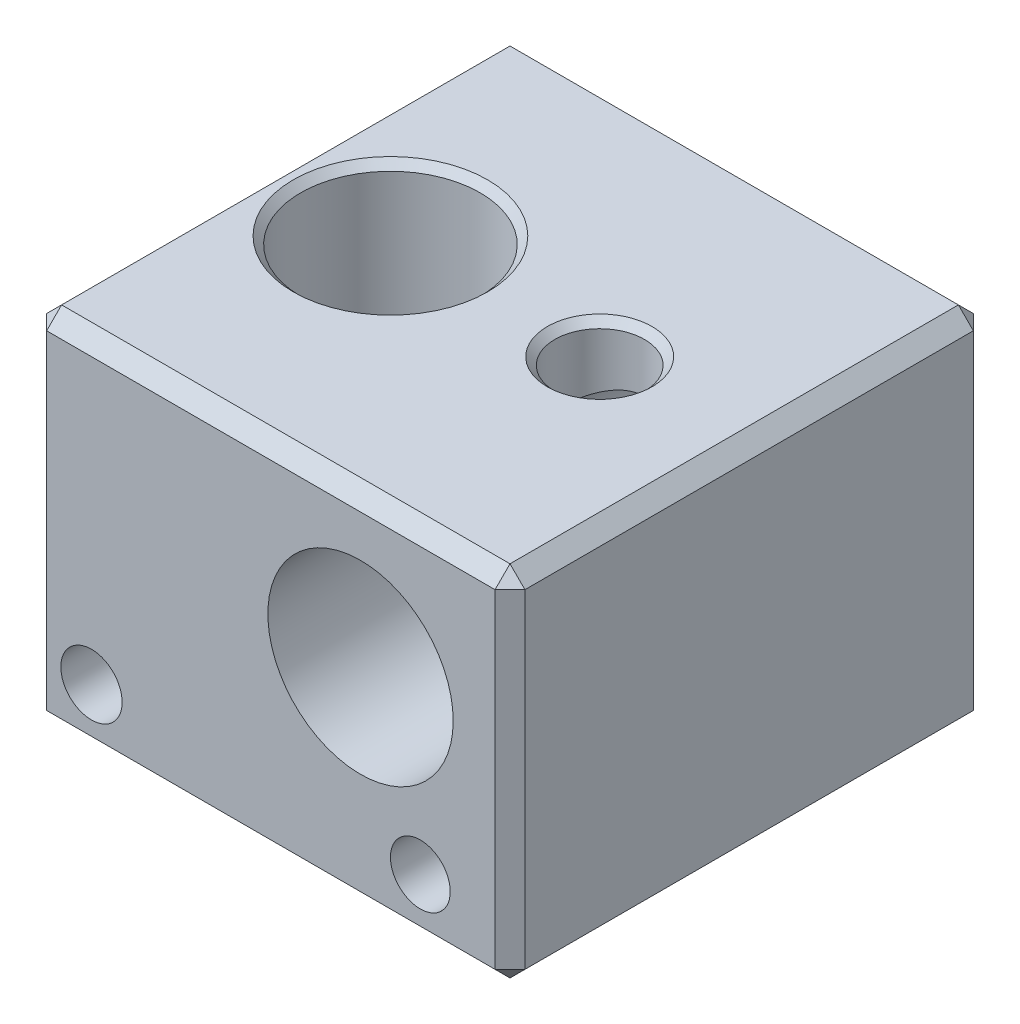
SolidWorks part; units mm, degrees
ref_plane "Front Plane" through (0, 0, 0) normal (0, 0, 1) x (1, 0, 0)
ref_plane "Top Plane" through (0, 0, 0) normal (0, 1, 0) x (1, 0, 0)
ref_plane "Right Plane" through (0, 0, 0) normal (1, 0, 0) x (0, 0, -1)
sketch "Sketch1" plane through (0, 0, 0) normal (0, 1, 0) x (1, 0, 0)
  line L1 (-8, 8) -> (8, 8)
  line L2 (-8, 8) -> (-8, -8)
  line L3 (-8, -8) -> (8, -8)
  line L4 (8, 8) -> (8, -8)
  line L5 (-8, 8) -> (8, -8) construction
  line L6 (-8, -8) -> (8, 8) construction
  circle A0 centre (-4, 0) radius 3
  point P0 (0, 0)
  dimension "D3" = 6
  dimension "D1" = 16
  dimension "D2" = 16
  dimension "D4" = 4
extrude "Boss-Extrude1" add sketch "Sketch1" along normal mid plane 12 contours L4 L1 L2 L3 A0
sketch "Sketch2" plane through (0, 0, 8) normal (0, 0, 1) x (1, 0, 0)
  line L0 (-8, -6) -> (8, -6) construction
  line L2 (-8, 6) -> (-8, -6) construction
  circle A2 centre (-6, -4) radius 1.25
  dimension "D4" = 2
  dimension "D6" = 2.5
  dimension "D5" = 2
hole_wizard "Tap Drill for M2.5x0.45 Tap1" positions "Sketch4" profile "Sketch3" hole size "M2.5x0.45" standard "ANSI Metric"
sketch "Sketch4" plane through (0, 0, 8) normal (0, 0, 1) x (1, 0, 0)
  line L0 (-8, 6) -> (-8, -6) construction
  line L1 (-8, -6) -> (8, -6) construction
  point P0 (-6, -4)
  dimension "D1" = 2
  dimension "D2" = 2
sketch "Sketch3" plane through (-6, -4, 8) normal (1, 0, 0) x (0, -1, 0)
  line L0 (0, 0) -> (0, 5.1159)
  line L1 (0, 5.1159) -> (1.025, 4.5)
  line L2 (1.025, 4.5) -> (1.025, 0)
  line L5 (1.025, 0) -> (0, 0)
  line L10 (0, 5.1159) -> (-1.025, 4.5) construction
  line L11 (0, -6.35) -> (0, 107.95) construction
  dimension "Hole Dia." = 2.05
  dimension "Hole Depth" = 4.5
  dimension "Drill Angle" = 118
sketch "Sketch5" plane through (0, 0, 8) normal (0, 0, 1) x (1, 0, 0)
  line L2 (-8, 6) -> (-8, -6) construction
  line L3 (-8, -6) -> (8, -6) construction
  circle A0 centre (3, 1) radius 3.1
  circle A1 centre (5, -4) radius 1
  dimension "D1" = 13
  dimension "D2" = 2
  dimension "D4" = 6.2
  dimension "D3" = 2
  dimension "D5" = 7
  dimension "D6" = 11
extrude "Cut-Extrude1" cut sketch "Sketch5" against normal through all
sketch "Sketch6" plane through (0, 6, 0) normal (0, 1, 0) x (1, 0, 0)
  line L0 (-8, 8) -> (-8, -8) construction
  circle A0 centre (3, 0) radius 1.5
  dimension "D1" = 3
  dimension "D2" = 11
extrude "Cut-Extrude2" cut sketch "Sketch6" against normal blind 6
chamfer "Chamfer1" distance 0.5 angle 45 12 edges at (0, -6, -8) (-8, -6, 0) (0, -6, 8) (8, -6, 0) (0, 6, 8) (8, 0, 8) (8, 6, 0) (8, 0, -8) (0, 6, -8) (-8, 0, -8) (-8, 6, 0) (-8, 0, 8)
chamfer "Chamfer2" distance 0.25 angle 45 3 edges at (-4, -6, 3) (3, 6, 1.5) (-4, 6, 3)
